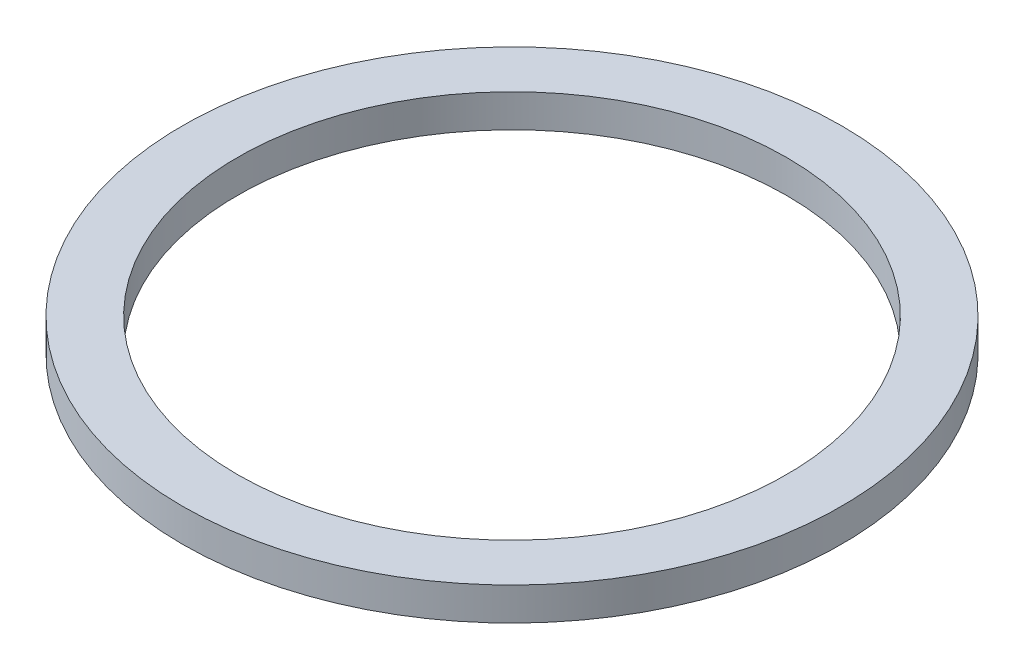
SolidWorks part; units mm, degrees
material "ABS"
ref_plane "前视基准面" through (0, 0, 0) normal (0, 0, 1) x (1, 0, 0)
ref_plane "上视基准面" through (0, 0, 0) normal (0, 1, 0) x (1, 0, 0)
ref_plane "右视基准面" through (0, 0, 0) normal (1, 0, 0) x (0, 0, -1)
sketch "草图1" plane through (0, 0, 0) normal (0, 1, 0) x (1, 0, 0)
  circle A0 centre (0, 0) radius 30
  circle A1 centre (0, 0) radius 25
  dimension "D1" = 50
  dimension "D2" = 5
extrude "凸台-拉伸1" add sketch "草图1" along normal blind 3
